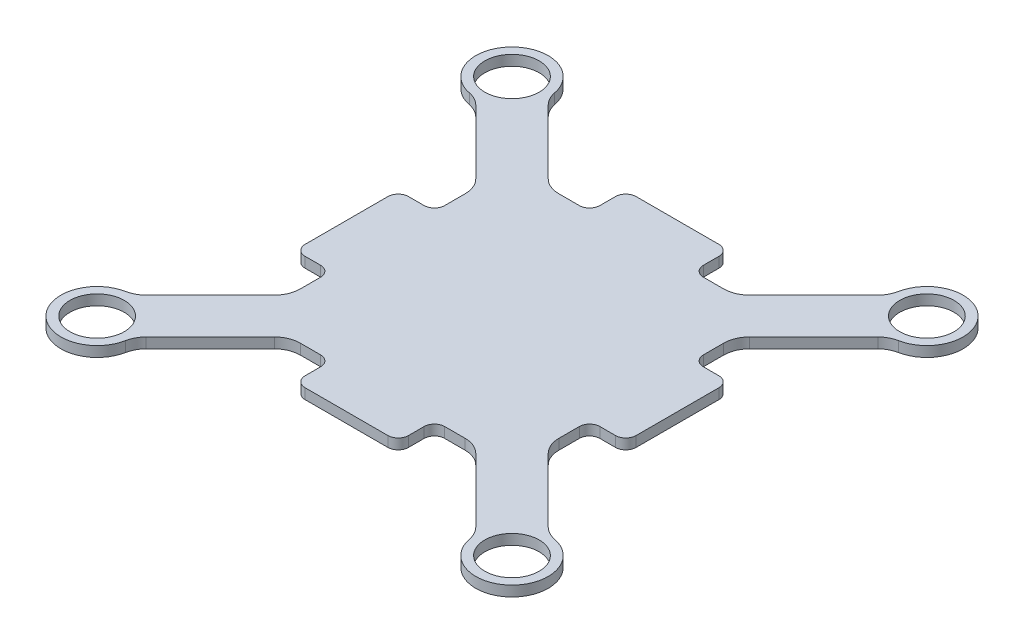
SolidWorks part; units mm, degrees
ref_plane "前视基准面" through (0, 0, 0) normal (0, 0, 1) x (1, 0, 0)
ref_plane "上视基准面" through (0, 0, 0) normal (0, 1, 0) x (1, 0, 0)
ref_plane "右视基准面" through (0, 0, 0) normal (1, 0, 0) x (0, 0, -1)
sketch "草图1" plane through (0, 0, 0) normal (0, 1, 0) x (1, 0, 0)
  line L11 (-15.9289, -25) -> (-12, -25)
  line L18 (25, 15.9289) -> (25, 12)
  line L19 (-25, 25) -> (25, -25) construction
  line L20 (-25, -25) -> (25, 25) construction
  line L26 (-45.0503, 45.0503) -> (-40.1005, 40.1005)
  line L27 (-38.857, 31.857) -> (-26.4645, 19.4645)
  line L33 (12, 25) -> (15.9289, 25)
  line L35 (-31.857, 38.857) -> (-19.4645, 26.4645)
  line L37 (-10, 30) -> (-10, 27)
  line L44 (-8, 32) -> (8, 32)
  line L46 (10, 27) -> (10, 30)
  line L47 (-15.9289, 25) -> (-12, 25)
  line L49 (-25, 15.9289) -> (-25, 12)
  line L50 (45.0503, 45.0503) -> (40.1005, 40.1005)
  line L51 (31.857, 38.857) -> (19.4645, 26.4645)
  line L52 (38.857, 31.857) -> (26.4645, 19.4645)
  line L53 (30, 10) -> (27, 10)
  line L54 (32, 8) -> (32, -8)
  line L55 (27, -10) -> (30, -10)
  line L56 (25, 15.9289) -> (25, 12)
  line L57 (45.0503, -45.0503) -> (40.1005, -40.1005)
  line L58 (38.857, -31.857) -> (26.4645, -19.4645)
  line L59 (31.857, -38.857) -> (19.4645, -26.4645)
  line L60 (10, -30) -> (10, -27)
  line L61 (8, -32) -> (-8, -32)
  line L62 (-10, -27) -> (-10, -30)
  line L63 (15.9289, -25) -> (12, -25)
  line L64 (-45.0503, -45.0503) -> (-40.1005, -40.1005)
  line L65 (-31.857, -38.857) -> (-19.4645, -26.4645)
  line L66 (-38.857, -31.857) -> (-26.4645, -19.4645)
  line L67 (-30, -10) -> (-27, -10)
  line L68 (-32, -8) -> (-32, 8)
  line L69 (-27, 10) -> (-30, 10)
  line L70 (-25, -15.9289) -> (-25, -12)
  line L71 (-25, -12) -> (-25, -15.9289)
  line L72 (25, -12) -> (25, -15.9289)
  line L73 (12, -25) -> (15.9289, -25)
  arc A2 (-33.2294, 41.4375) -> (-41.4375, 33.2294) centre (-40.1005, 40.1005) ccw
  circle A3 centre (-40.1005, 40.1005) radius 5.25
  arc A4 (41.4375, 33.2294) -> (33.2294, 41.4375) centre (40.1005, 40.1005) ccw
  circle A5 centre (40.1005, 40.1005) radius 5.25
  arc A6 (33.2294, -41.4375) -> (41.4375, -33.2294) centre (40.1005, -40.1005) ccw
  circle A7 centre (40.1005, -40.1005) radius 5.25
  arc A8 (-41.4375, -33.2294) -> (-33.2294, -41.4375) centre (-40.1005, -40.1005) ccw
  circle A9 centre (-40.1005, -40.1005) radius 5.25
  arc A10 (-10, 27) -> (-12, 25) centre (-12, 27) cw
  arc A11 (-10, 30) -> (-8, 32) centre (-8, 30) cw
  arc A12 (8, 32) -> (10, 30) centre (8, 30) cw
  arc A13 (12, 25) -> (10, 27) centre (12, 27) cw
  arc A14 (27, 10) -> (25, 12) centre (27, 12) cw
  arc A15 (30, 10) -> (32, 8) centre (30, 8) cw
  arc A16 (27, -10) -> (25, -12) centre (27, -12) ccw
  arc A17 (32, -8) -> (30, -10) centre (30, -8) cw
  arc A18 (10, -27) -> (12, -25) centre (12, -27) cw
  arc A19 (10, -30) -> (8, -32) centre (8, -30) cw
  arc A20 (-8, -32) -> (-10, -30) centre (-8, -30) cw
  arc A21 (-10, -27) -> (-12, -25) centre (-12, -27) ccw
  arc A22 (-27, 10) -> (-25, 12) centre (-27, 12) ccw
  arc A23 (-27, -10) -> (-25, -12) centre (-27, -12) cw
  arc A24 (-30, -10) -> (-32, -8) centre (-30, -8) cw
  arc A25 (-32, 8) -> (-30, 10) centre (-30, 8) cw
  arc A26 (-26.4645, -19.4645) -> (-25, -15.9289) centre (-30, -15.9289) ccw
  arc A27 (-38.857, -31.857) -> (-41.4375, -33.2294) centre (-42.3925, -28.3214) cw
  arc A28 (-31.857, -38.857) -> (-33.2294, -41.4375) centre (-28.3214, -42.3925) ccw
  arc A29 (-19.4645, -26.4645) -> (-15.9289, -25) centre (-15.9289, -30) cw
  arc A30 (19.4645, -26.4645) -> (15.9289, -25) centre (15.9289, -30) ccw
  arc A31 (31.857, -38.857) -> (33.2294, -41.4375) centre (28.3214, -42.3925) cw
  arc A32 (38.857, -31.857) -> (41.4375, -33.2294) centre (42.3925, -28.3214) ccw
  arc A33 (26.4645, -19.4645) -> (25, -15.9289) centre (30, -15.9289) cw
  arc A34 (26.4645, 19.4645) -> (25, 15.9289) centre (30, 15.9289) ccw
  arc A35 (38.857, 31.857) -> (41.4375, 33.2294) centre (42.3925, 28.3214) cw
  arc A36 (31.857, 38.857) -> (33.2294, 41.4375) centre (28.3214, 42.3925) ccw
  arc A37 (19.4645, 26.4645) -> (15.9289, 25) centre (15.9289, 30) cw
  arc A38 (-19.4645, 26.4645) -> (-15.9289, 25) centre (-15.9289, 30) ccw
  arc A39 (-31.857, 38.857) -> (-33.2294, 41.4375) centre (-28.3214, 42.3925) cw
  arc A40 (-26.4645, 19.4645) -> (-25, 15.9289) centre (-30, 15.9289) cw
  arc A41 (-38.857, 31.857) -> (-41.4375, 33.2294) centre (-42.3925, 28.3214) ccw
  point P0 (0, 0)
  point P8 (-20.0503, 20.0503)
  point P13 (20.0503, 20.0503)
  point P33 (20.0503, -20.0503)
  point P45 (-20.0503, -20.0503)
  point P56 (0, 0)
  point P120 (-33.1005, 40.1005)
  point P125 (-40.1005, 33.1005)
  dimension "D3" = 5
  dimension "D4" = 7
  dimension "D2" = 2
  dimension "D1" = 4
extrude "凸台-拉伸1" add sketch "草图1" along normal blind 2
